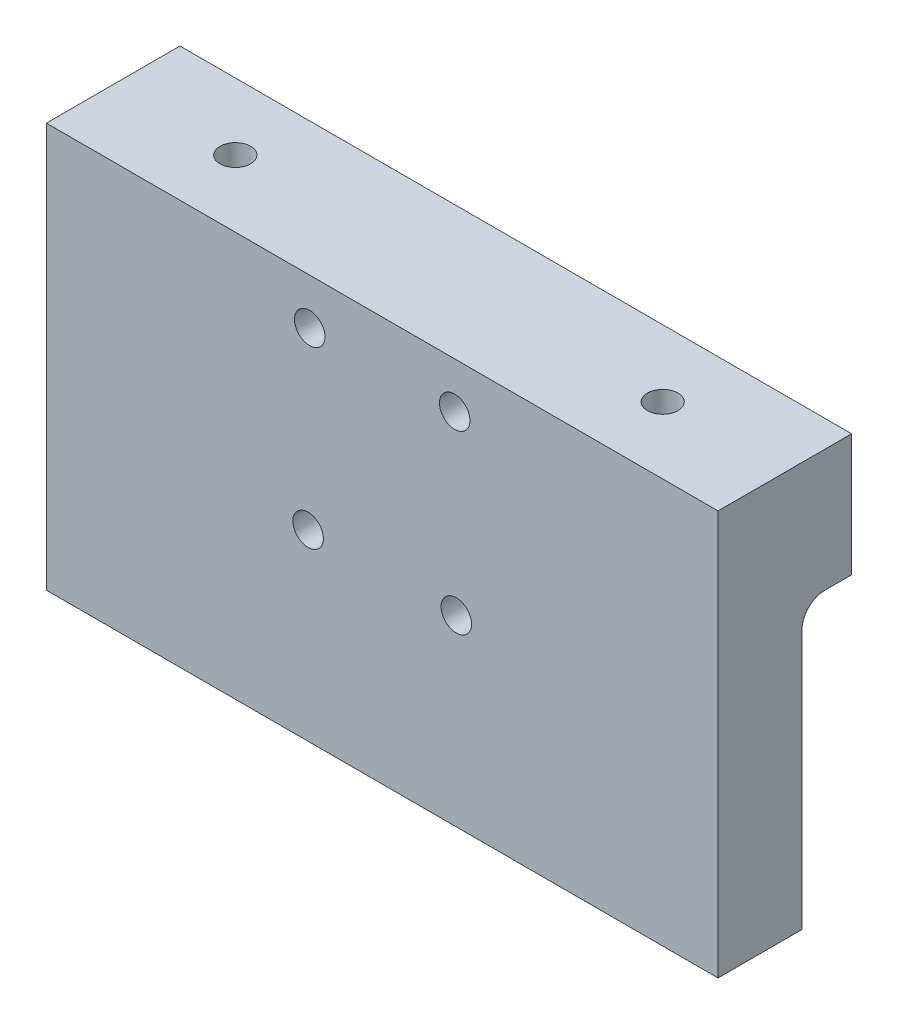
SolidWorks part; units mm, degrees
ref_plane "Front Plane" through (0, 0, 0) normal (0, 0, 1) x (1, 0, 0)
ref_plane "Top Plane" through (0, 0, 0) normal (0, 1, 0) x (1, 0, 0)
ref_plane "Right Plane" through (0, 0, 0) normal (1, 0, 0) x (0, 0, -1)
sketch "Sketch1" plane through (0, 0, 0) normal (1, 0, 0) x (0, 0, -1)
  line L1 (11, 53) -> (-11, 53)
  line L2 (11, 15) -> (11, -53)
  line L3 (11, -53) -> (-11, -53)
  line L4 (-11, 53) -> (-11, -53)
  line L7 (11, 53) -> (24, 53)
  line L9 (17, 21) -> (24, 21)
  line L10 (24, 53) -> (24, 21)
  arc A0 (17, 21) -> (11, 15) centre (17, 15) ccw
  point P0 (0, 0)
  dimension "D5" = 6
  dimension "D1" = 22
  dimension "D2" = 106
  dimension "D3" = 32
  dimension "D4" = 35
extrude "Boss-Extrude1" add sketch "Sketch1" along normal blind 176
sketch "Sketch2" plane through (0, 0, -11) normal (0, 0, -1) x (-1, 0, 0)
  line L0 (-88, -53) -> (-88, 53) construction
  line L1 (-176, -53) -> (0, -53) construction
  line L2 (-176, 53) -> (0, 53) construction
  circle A0 centre (-69, 41) radius 4
  circle A1 centre (-107, 41) radius 4
  circle A2 centre (-68.5806, -5) radius 4
  circle A3 centre (-107.4194, -5) radius 4
  dimension "D1" = 8
  dimension "D2" = 8
  dimension "D5" = 8
  dimension "D3" = 12
  dimension "D4" = 12
  dimension "D6" = 19
  dimension "D7" = 19
  dimension "D8" = 46
extrude "Cut-Extrude1" cut sketch "Sketch2" against normal mid plane 180
sketch "Sketch3" plane through (0, 53, 0) normal (0, 1, 0) x (1, 0, 0)
  line L0 (88, -11) -> (88, 24) construction
  line L1 (176, -11) -> (0, -11) construction
  line L2 (176, 24) -> (0, 24) construction
  circle A0 centre (32, 6.5) radius 4
  circle A1 centre (144, 6.5) radius 4
  dimension "D1" = 8
  dimension "D2" = 56
extrude "Cut-Extrude2" cut sketch "Sketch3" against normal blind 12
